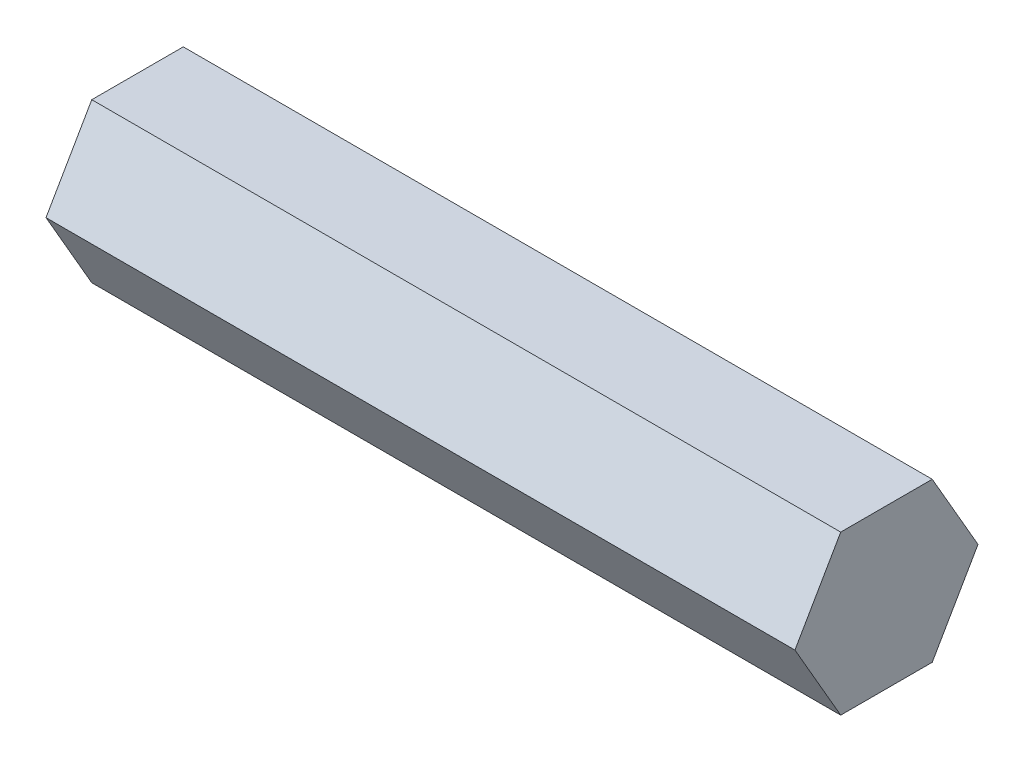
SolidWorks part; units mm, degrees
material "2014-T6"
ref_plane "Alzado" through (0, 0, 0) normal (0, 0, 1) x (1, 0, 0)
ref_plane "Planta" through (0, 0, 0) normal (0, 1, 0) x (1, 0, 0)
ref_plane "Vista lateral" through (0, 0, 0) normal (1, 0, 0) x (0, 0, -1)
sketch "Croquis1" plane through (0, 0, 0) normal (1, 0, 0) x (0, 0, -1)
  line L1 (7.3323, 0) -> (3.6662, 6.35)
  line L2 (3.6662, 6.35) -> (-3.6662, 6.35)
  line L3 (-3.6662, 6.35) -> (-7.3323, 0)
  line L4 (-7.3323, 0) -> (-3.6662, -6.35)
  line L5 (-3.6662, -6.35) -> (3.6662, -6.35)
  line L6 (3.6662, -6.35) -> (7.3323, 0)
  circle A0 centre (0, 0) radius 6.35 construction
  dimension "D1" = 12.7
extrude "Saliente-Extruir1" add sketch "Croquis1" along normal blind 60
